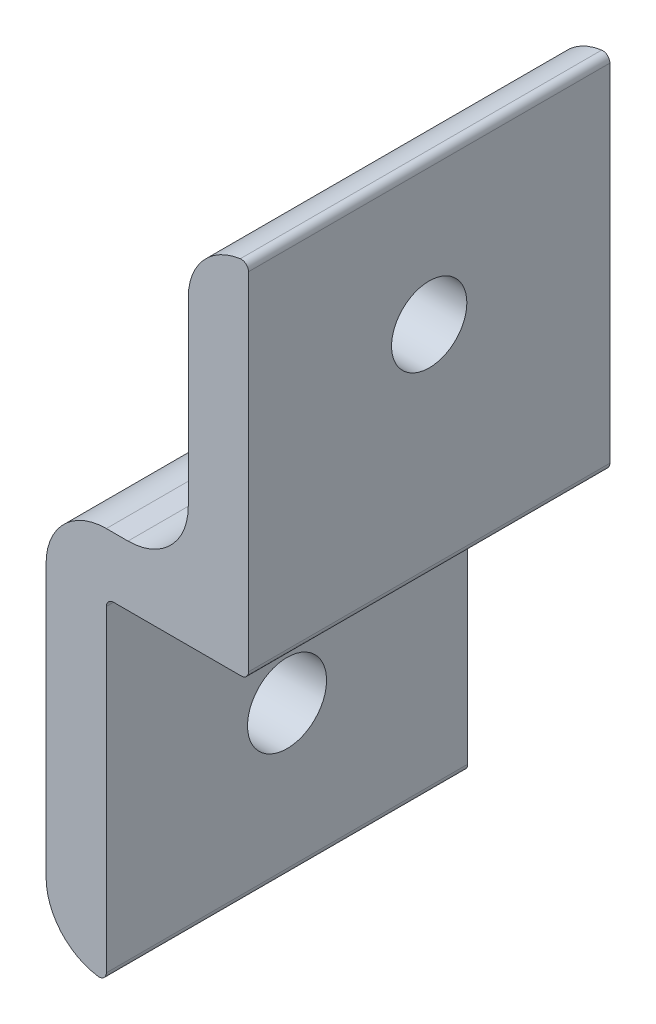
SolidWorks part; units mm, degrees
ref_plane "Front Plane" through (0, 0, 0) normal (0, 0, 1) x (1, 0, 0)
ref_plane "Top Plane" through (0, 0, 0) normal (0, 1, 0) x (1, 0, 0)
ref_plane "Right Plane" through (0, 0, 0) normal (1, 0, 0) x (0, 0, -1)
ref_plane "Plane1" through (0, 0, 0) normal (0, 0, -1) x (-1, 0, 0)
sketch "Sketch1" plane through (0, 0, 0) normal (0, 0, -1) x (-1, 0, 0)
  line L0 (21.0747, -31.5102) -> (6.0887, -31.5102)
  line L1 (6.0887, -31.5102) -> (6.0887, -6.1102)
  line L2 (-0.2613, 0.2398) -> (-0.2613, -37.8602)
  line L3 (-0.2613, -37.8602) -> (14.7247, -37.8602)
  line L4 (14.7247, -37.8602) -> (14.7247, -72.8868)
  line L5 (21.0747, -66.5368) -> (21.0747, -31.5102)
  arc A0 (6.0887, -6.1102) -> (-0.2613, 0.2398) centre (-0.2613, -6.1102) ccw
  arc A1 (14.7247, -72.8868) -> (21.0747, -66.5368) centre (14.7247, -66.5368) ccw
extrude "Boss-Extrude1" add sketch "Sketch1" against normal blind 38.1
hole_wizard "M7 Clearance Hole1" positions "Sketch3" profile "Sketch2" hole size "M7" standard "Ansi Metric"
sketch "Sketch3" plane through (0.2613, 0, 0) normal (1, 0, 0) x (0, 0, -1)
  point P0 (-19.05, -14.9062)
sketch "Sketch2" plane through (0.2613, -14.9062, 19.05) normal (0, 1, 0) x (0, 0, -1)
  line L0 (0, 0) -> (0, 21.336)
  line L1 (0, 21.336) -> (3.9687, 21.336)
  line L2 (3.9687, 21.336) -> (3.9687, 0)
  line L5 (3.9687, 0) -> (0, 0)
  line L11 (0, -6.35) -> (0, 107.95) construction
  dimension "Thru Hole Dia." = 7.9375
  dimension "Thru Hole Depth" = 21.336
hole_wizard "Hole1" positions "Sketch5" profile "Sketch4" legacy
sketch "Sketch5" plane through (-21.0747, 0, 0) normal (-1, 0, 0) x (0, 0, 1)
  point P0 (19.05, -56.9635)
sketch "Sketch4" plane through (-21.0747, -56.9635, 19.05) normal (0, 1, 0) x (0, 0, 1)
  line L0 (0, 0) -> (0, 21.336)
  line L1 (0, 21.336) -> (4.1656, 21.336)
  line L2 (4.1656, 21.336) -> (4.1656, 0)
  line L3 (4.1656, 0) -> (0, 0)
  line L4 (0, 110) -> (0, -10) construction
  dimension "Diameter" = 8.3312
  dimension "Depth" = 21.336
fillet "Fillet1" radius 0.762 4 edges at (0.2613, -37.8602, 19.05) (0.2613, 0.2398, 19.05) (-14.7247, -37.8602, 19.05) (-14.7247, -72.8868, 19.05)
fillet "Fillet2" radius 6.35 2 edges at (-6.0887, -31.5102, 19.05) (-21.0747, -31.5102, 19.05)
sketch "Sketch6" plane through (-21.0747, 0, 0) normal (-1, 0, 0) x (0, 0, 1)
  line L0 (19.05, -37.8602) -> (19.05, -66.5368)
  line L1 (38.1, -37.8602) -> (0, -37.8602) construction
  line L2 (38.1, -66.5368) -> (0, -66.5368) construction
ref_plane "midplane" through (0, 0, 19.05) normal (0, 0, 1) x (1, 0, 0)
